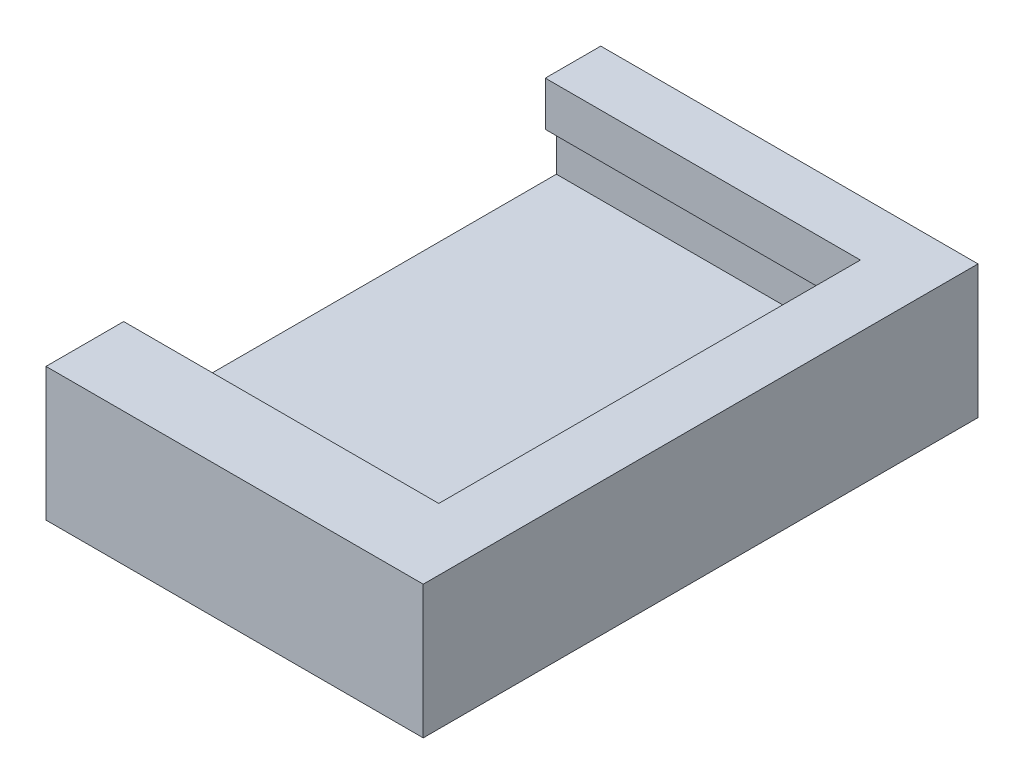
SolidWorks part; units mm, degrees
ref_plane "Front Plane" through (0, 0, 0) normal (0, 0, 1) x (1, 0, 0)
ref_plane "Top Plane" through (0, 0, 0) normal (0, 1, 0) x (1, 0, 0)
ref_plane "Right Plane" through (0, 0, 0) normal (1, 0, 0) x (0, 0, -1)
sketch "Sketch1" plane through (0, 0, 0) normal (0, 1, 0) x (1, 0, 0)
  line L1 (-9.525, -13.335) -> (9.525, -13.335) construction
  line L2 (-9.525, -13.335) -> (-9.525, 13.335) construction
  line L3 (-9.525, 13.335) -> (9.525, 13.335) construction
  line L4 (9.525, -13.335) -> (9.525, 13.335) construction
  line L5 (-9.525, -13.335) -> (9.525, 13.335) construction
  line L6 (-9.525, 13.335) -> (9.525, -13.335) construction
  line L7 (12.065, -15.875) -> (-12.065, -15.875)
  line L8 (12.065, -15.875) -> (12.065, 15.875)
  line L9 (12.065, 15.875) -> (-12.065, 15.875)
  line L10 (-12.065, -15.875) -> (-12.065, 15.875)
  line L11 (12.065, -15.875) -> (-12.065, 15.875) construction
  line L12 (12.065, 15.875) -> (-12.065, -15.875) construction
  point P0 (0, 0)
  point P6 (0, 0)
  dimension "D1" = 19.05
  dimension "D2" = 26.67
  dimension "D3" = 2.54
  dimension "D4" = 2.54
extrude "Boss-Extrude1" add sketch "Sketch1" along normal blind 2.54
sketch "Sketch2" plane through (0, 2.54, 0) normal (0, 1, 0) x (1, 0, 0)
  line L0 (-12.065, 15.875) -> (-12.065, 13.335)
  line L1 (9.525, -13.335) -> (-9.525, -13.335)
  line L2 (9.525, -13.335) -> (9.525, 13.335)
  line L3 (9.525, 13.335) -> (-9.525, 13.335)
  line L4 (-9.525, -13.335) -> (-9.525, 13.335) construction
  line L5 (9.525, -13.335) -> (-9.525, 13.335) construction
  line L6 (9.525, 13.335) -> (-9.525, -13.335) construction
  line L7 (12.065, -15.875) -> (-12.065, -15.875)
  line L8 (12.065, -15.875) -> (12.065, 15.875)
  line L9 (12.065, 15.875) -> (-12.065, 15.875)
  line L10 (-12.065, -15.875) -> (-12.065, 15.875) construction
  line L11 (12.065, -15.875) -> (-12.065, 15.875) construction
  line L12 (12.065, 15.875) -> (-12.065, -15.875) construction
  line L13 (-12.065, 13.335) -> (-9.525, 13.335)
  line L14 (-12.065, -15.875) -> (-12.065, -13.335)
  line L15 (-12.065, -13.335) -> (-9.525, -13.335)
  point P0 (0, 0)
  point P6 (0, 0)
  dimension "D1" = 26.67
  dimension "D2" = 19.05
extrude "Boss-Extrude2" add sketch "Sketch2" along normal blind 2.54 contours L2 L3 L13 L0 L9 L8 L7 L14 L15 L1
sketch "Sketch3" plane through (-12.065, 0, 0) normal (-1, 0, 0) x (0, 0, 1)
  line L1 (-15.875, 0) -> (15.875, 0)
  line L2 (-15.875, 0) -> (-15.875, 5.08)
  line L3 (-15.875, 5.08) -> (15.875, 5.08)
  line L4 (15.875, 0) -> (15.875, 5.08)
extrude "Cut-Extrude1" cut sketch "Sketch3" against normal blind 2.54
sketch "Sketch4" plane through (0, 5.08, 0) normal (0, 1, 0) x (1, 0, 0)
  line L0 (-9.525, 15.875) -> (-9.525, 12.7)
  line L1 (12.065, 15.875) -> (-9.525, 15.875)
  line L2 (12.065, 15.875) -> (12.065, -15.875)
  line L3 (12.065, -15.875) -> (-9.525, -15.875)
  line L4 (-9.525, 15.875) -> (-9.525, -15.875) construction
  line L5 (8.509, 12.7) -> (-9.525, 12.7)
  line L6 (8.509, 12.7) -> (8.509, -11.43)
  line L7 (8.509, -11.43) -> (-9.525, -11.43)
  line L8 (-9.525, 12.7) -> (-9.525, -11.43) construction
  line L9 (-9.525, -11.43) -> (-9.525, -15.875)
  dimension "D1" = 3.175
  dimension "D2" = 3.556
  dimension "D3" = 4.445
extrude "Boss-Extrude3" add sketch "Sketch4" along normal blind 2.54
sketch "Sketch5" plane through (0, 0, 0) normal (0, -1, 0) x (-1, 0, 0)
  line L0 (-1.27, -15.875) -> (-1.27, 15.875) construction
  line L1 (9.525, -15.875) -> (-12.065, -15.875) construction
  line L2 (-12.065, 15.875) -> (9.525, 15.875) construction
  line L3 (-1.27, 0) -> (-12.065, 0) construction
  line L4 (-12.065, -15.875) -> (-12.065, 15.875) construction
  line L5 (-12.065, 6.35) -> (-12.065, -6.35)
  line L6 (-12.065, 0) -> (-24.765, 0) construction
  line L7 (-12.065, -6.35) -> (-18.415, -6.35)
  line L8 (-12.065, 6.35) -> (-18.415, 6.35)
  line L9 (9.525, 6.35) -> (15.875, 6.35)
  line L10 (9.525, 6.35) -> (9.525, -6.35)
  line L11 (9.525, -6.35) -> (15.875, -6.35)
  circle A0 centre (-18.415, 0) radius 6.35 construction
  arc A1 (-18.415, -6.35) -> (-24.765, 0) centre (-18.415, 0) cw
  arc A2 (-18.415, 6.35) -> (-24.765, 0) centre (-18.415, 0) ccw
  circle A3 centre (-18.415, 0) radius 2.5527
  circle A4 centre (15.875, 0) radius 2.5527
  arc A5 (15.875, 6.35) -> (22.225, 0) centre (15.875, 0) cw
  arc A6 (15.875, -6.35) -> (22.225, 0) centre (15.875, 0) ccw
  line M11 (-12.065, 15.875) -> (-12.065, -15.875)
  dimension "D2" = 5.1054
  dimension "D1" = 6.35
extrude "Boss-Extrude4" add sketch "Sketch5" against normal blind 2.54 contours L8 A2 A1 L7 A3 M11 | A5 A6 L11 L10 L9 | A4
